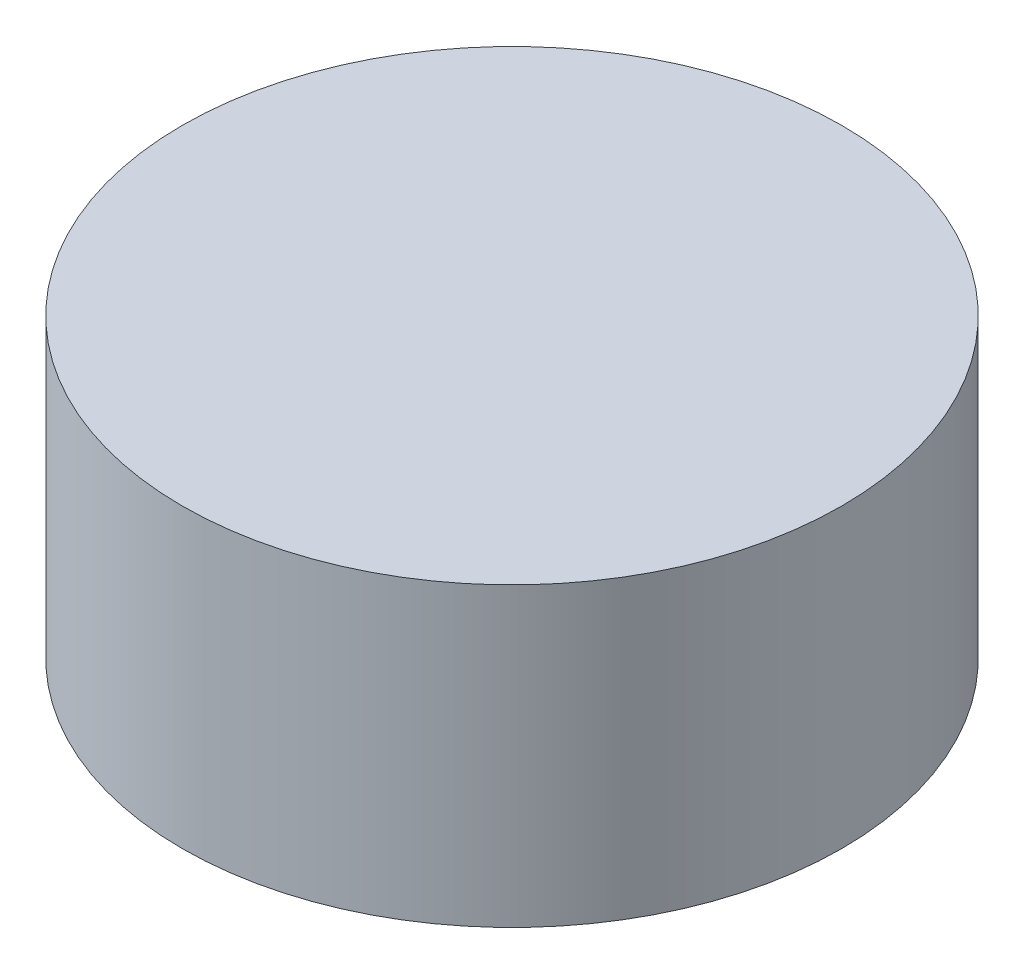
SolidWorks part; units mm, degrees
ref_plane "Front Plane" through (0, 0, 0) normal (0, 0, 1) x (1, 0, 0)
ref_plane "Top Plane" through (0, 0, 0) normal (0, 1, 0) x (1, 0, 0)
ref_plane "Right Plane" through (0, 0, 0) normal (1, 0, 0) x (0, 0, -1)
other "Configuration Table"
sketch "Sketch1" plane through (0, 0, 0) normal (0, 1, 0) x (1, 0, 0)
  circle A0 centre (0, 0) radius 20
extrude "VNT_koruk_dudak_D40" add sketch "Sketch1" along normal blind 18 separate body
